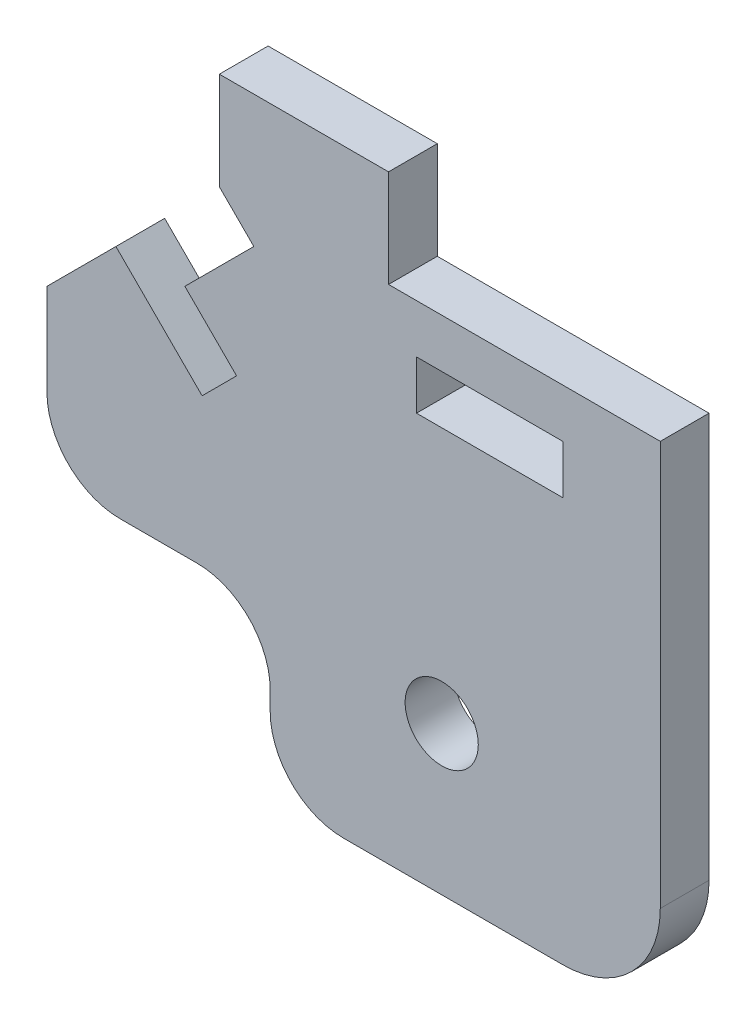
SolidWorks part; units mm, degrees
material "Acrylic (Medium-high impact)"
ref_plane "Front Plane" through (0, 0, 0) normal (0, 0, 1) x (1, 0, 0)
ref_plane "Top Plane" through (0, 0, 0) normal (0, 1, 0) x (1, 0, 0)
ref_plane "Right Plane" through (0, 0, 0) normal (1, 0, 0) x (0, 0, -1)
sketch "Model" plane through (0, 0, 0) normal (0, 0, 1) x (1, 0, 0)
  line L269 (1964.4027, 1171.5266) -> (1960.8672, 1175.0622)
  line L270 (1972.0492, 1179.3048) -> (1983.1956, 1179.3048)
  line L271 (1964.1956, 1165.4764) -> (1963.8672, 1165.4764)
  line L272 (1979.1956, 1158.7137) -> (1970.1956, 1158.7137)
  line L273 (1960.8672, 1175.0622) -> (1958.0388, 1172.2337)
  line L274 (1961.0388, 1165.4764) -> (1963.8672, 1165.4764)
  line L275 (1965.8169, 1172.9408) -> (1963.6956, 1175.0622)
  line L276 (1966.5241, 1177.8906) -> (1965.1098, 1179.3048)
  line L277 (1958.0388, 1168.4764) -> (1958.0388, 1172.2337)
  line L278 (1967.1956, 1161.7137) -> (1967.1956, 1162.4764)
  line L279 (1983.1956, 1179.3048) -> (1983.1956, 1162.7137)
  line L280 (1965.1098, 1183.3048) -> (1972.0492, 1183.3048)
  line L281 (1979.1956, 1175.3048) -> (1979.1956, 1177.3048)
  line L282 (1979.1956, 1175.3048) -> (1973.1956, 1175.3048)
  line L283 (1973.1956, 1175.3048) -> (1973.1956, 1177.3048)
  line L284 (1973.1956, 1177.3048) -> (1979.1956, 1177.3048)
  line L301 (1963.6956, 1175.0622) -> (1966.5241, 1177.8906)
  line L302 (1965.1098, 1179.3048) -> (1965.1098, 1183.3048)
  line L303 (1964.4027, 1171.5266) -> (1965.8169, 1172.9408)
  line L559 (1972.0492, 1179.3048) -> (1972.0492, 1183.3048)
  circle A124 centre (1974.2305, 1164.7961) radius 1.5
  arc A125 (1979.1956, 1158.7137) -> (1983.1956, 1162.7137) centre (1979.1956, 1162.7137) ccw
  arc A126 (1967.1956, 1161.7137) -> (1970.1956, 1158.7137) centre (1970.1956, 1161.7137) ccw
  arc A127 (1967.1956, 1162.4764) -> (1964.1956, 1165.4764) centre (1964.1956, 1162.4764) ccw
  arc A128 (1958.0388, 1168.4764) -> (1961.0388, 1165.4764) centre (1961.0388, 1168.4764) ccw
extrude "Boss-Extrude1" add sketch "Model" along normal blind 2
